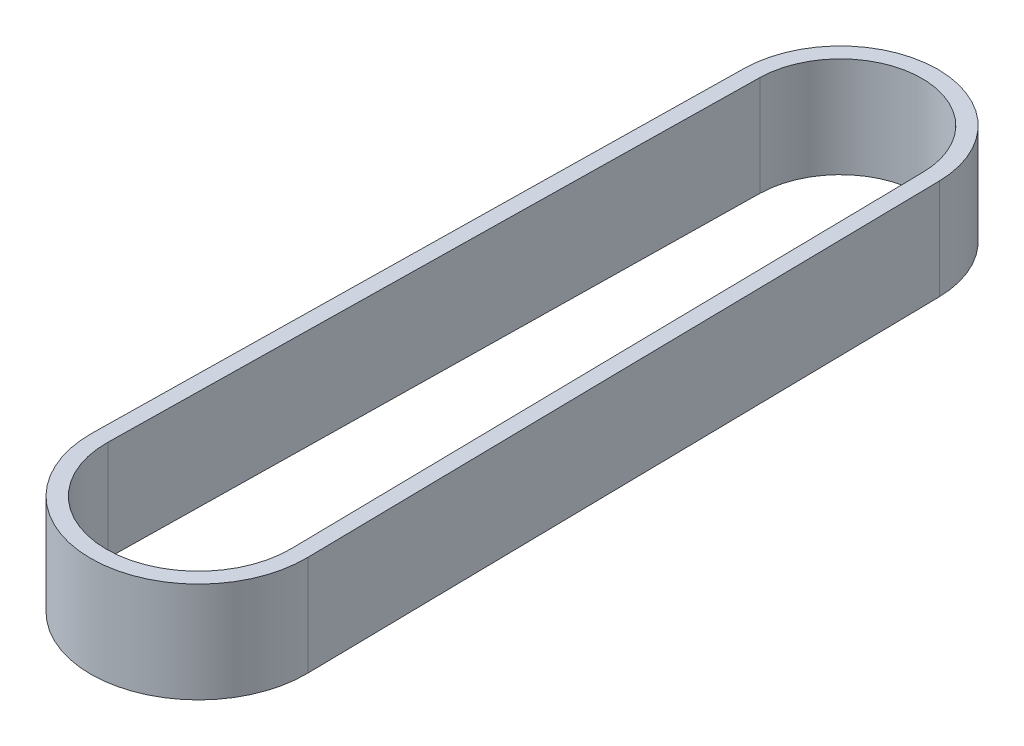
SolidWorks part; units mm, degrees
material "NEOPRENE"
ref_plane "Plan de face" through (0, 0, 0) normal (0, 0, 1) x (1, 0, 0)
ref_plane "Plan de dessus" through (0, 0, 0) normal (0, 1, 0) x (1, 0, 0)
ref_plane "Plan de droite" through (0, 0, 0) normal (1, 0, 0) x (0, 0, -1)
sketch "Esquisse1" plane through (0, 0, 0) normal (0, 1, 0) x (1, 0, 0)
  line L0 (5.8193, -12.0076) -> (5.1743, 28.6173)
  line L1 (-5.1743, 28.6173) -> (-5.8193, -12.0076)
  line L2 (0, 28.5351) -> (0, -12.1) construction
  line L3 (6.8191, -11.9917) -> (6.1742, 28.6331)
  line L4 (-6.1742, 28.6331) -> (-6.8191, -11.9917)
  arc A0 (5.1743, 28.6173) -> (-5.1743, 28.6173) centre (0, 28.5351) ccw
  arc A1 (-5.8193, -12.0076) -> (5.8193, -12.0076) centre (0, -12.1) ccw
  arc A4 (6.1742, 28.6331) -> (-6.1742, 28.6331) centre (0, 28.5351) ccw
  arc A5 (-6.8191, -11.9917) -> (6.8191, -11.9917) centre (0, -12.1) ccw
  circle A6 centre (0, -12.1) radius 5.82 construction
  circle A7 centre (0, 28.5351) radius 5.175 construction
  point P7 (0, 28.1351)
  dimension "D1" = 40.63
  dimension "D2" = 1
extrude "Boss.-Extru.1" add sketch "Esquisse1" along normal mid plane 6.35
